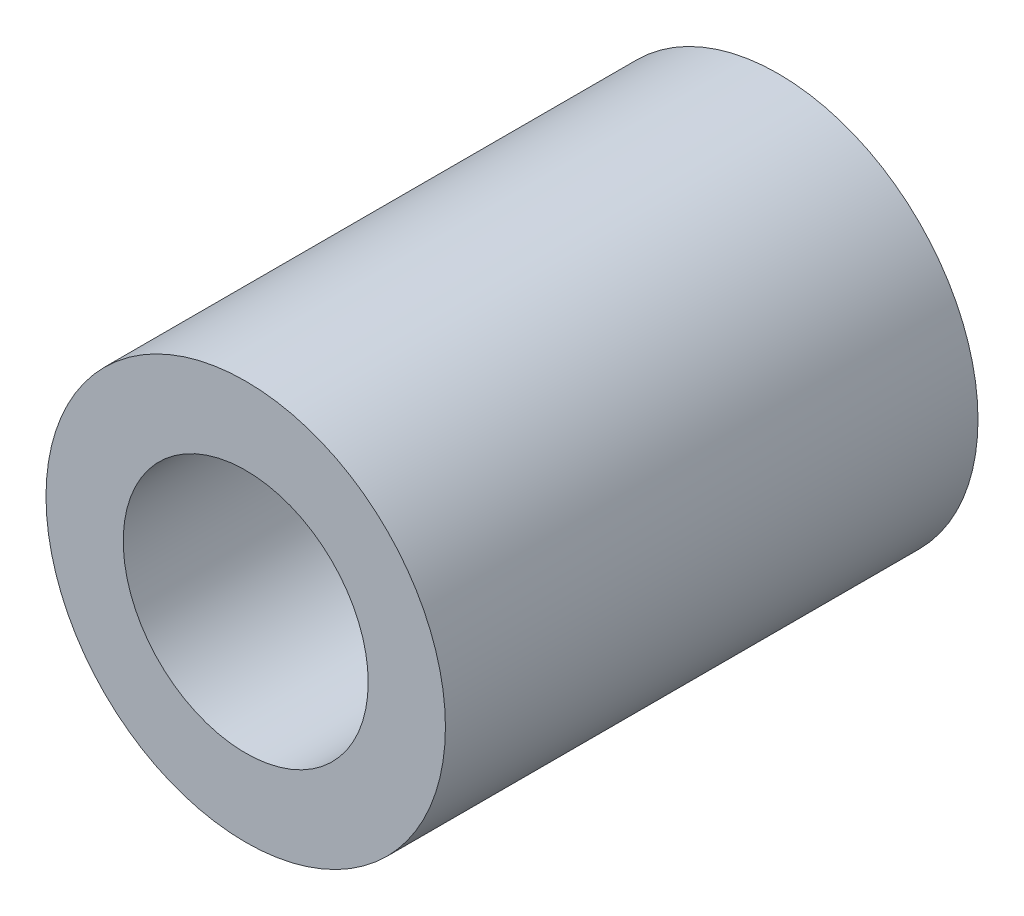
SolidWorks part; units mm, degrees
ref_plane "Front Plane" through (0, 0, 0) normal (0, 0, 1) x (1, 0, 0)
ref_plane "Top Plane" through (0, 0, 0) normal (0, 1, 0) x (1, 0, 0)
ref_plane "Right Plane" through (0, 0, 0) normal (1, 0, 0) x (0, 0, -1)
sketch "Sketch1" plane through (0, 0, 0) normal (0, 0, 1) x (1, 0, 0)
  circle A0 centre (0, 0) radius 2.3813
  circle A1 centre (0, 0) radius 1.4605
  dimension "OD" = 4.7625
  dimension "ID" = 2.921
extrude "Extrude1" add sketch "Sketch1" along normal mid plane 6.35
sketch "Sketch2" plane through (0, 0, 0) normal (1, 0, 0) x (0, 0, -1)
  line L0 (-3.175, -1.4605) -> (3.175, -1.4605) construction
  line L3 (3.175, 1.4605) -> (-3.175, 1.4605) construction
  line L5 (-3.175, -1.4605) -> (3.175, -1.4605)
  line L6 (3.175, 1.4605) -> (-3.175, 1.4605)
sketch "Sketch4" plane through (0, 0, 3.175) normal (0, 0, 1) x (1, 0, 0)
  line L0 (0, 0) -> (-1.0327, 1.0327)
  line L1 (0, -2.1828) -> (0, 2.1828) construction
  circle A0 centre (0, 0) radius 1.4605 construction
  dimension "D1" = 45
